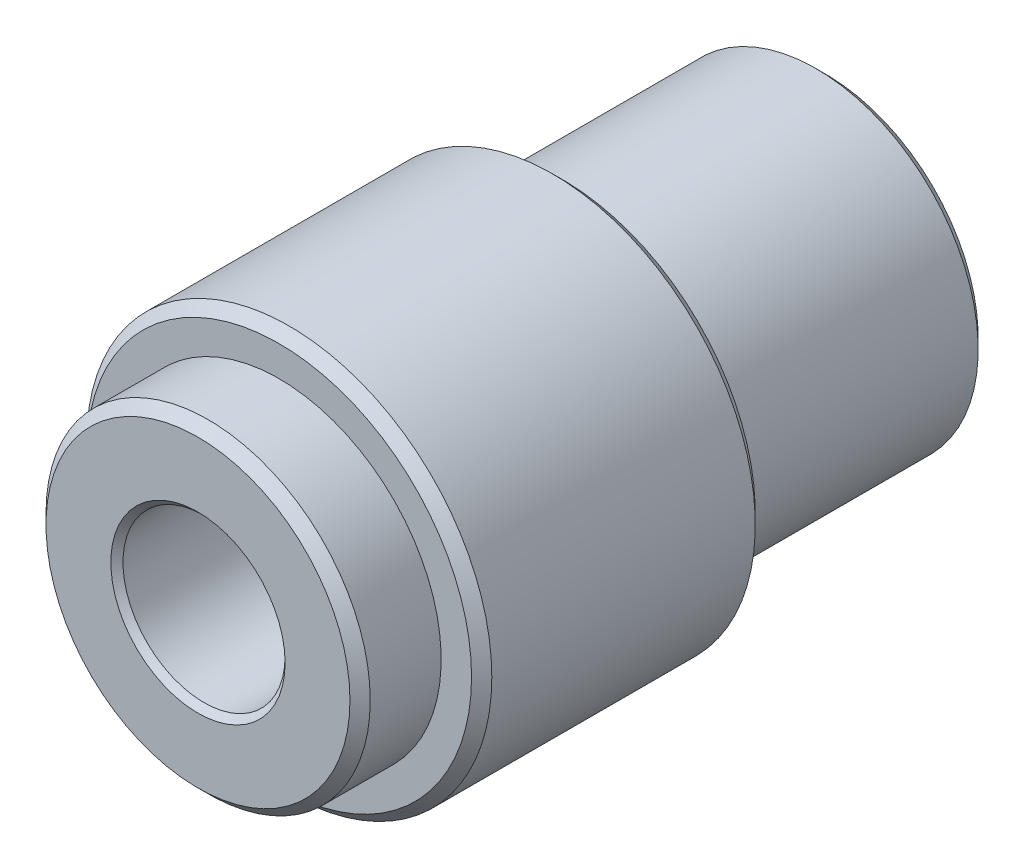
SolidWorks part; units mm, degrees
material "A2017"
ref_plane "正面" through (0, 0, 0) normal (0, 0, 1) x (1, 0, 0)
ref_plane "平面" through (0, 0, 0) normal (0, 1, 0) x (1, 0, 0)
ref_plane "右側面" through (0, 0, 0) normal (1, 0, 0) x (0, 0, -1)
sketch "ｽｹｯﾁ1" plane through (0, 0, 0) normal (1, 0, 0) x (0, 0, -1)
  line L0 (0, 0) -> (15.5, 0) construction
  line L1 (0, 0) -> (0, 4)
  line L2 (0, 4) -> (2, 4)
  line L3 (2, 4) -> (2, 5)
  line L4 (2, 5) -> (9, 5)
  line L5 (9, 5) -> (9, 4)
  line L6 (9, 4) -> (15.5, 4)
  line L7 (15.5, 4) -> (15.5, 0)
  line L8 (15.5, 0) -> (0, 0)
  dimension "D1" = 8
  dimension "D2" = 10
  dimension "D3" = 7
  dimension "D4" = 2
  dimension "D5" = 6.5
revolve "回転1" add sketch "ｽｹｯﾁ1" angle 360 about L8
chamfer "面取り1" distance 0.25 angle 45 4 edges at (-4, 0, -15.5) (-4, 0, 0) (-5, 0, -9) (-5, 0, -2)
sketch "ｽｹｯﾁ2" plane through (0, 0, 0) normal (0, 0, 1) x (1, 0, 0)
  circle A0 centre (0, 0) radius 2
  dimension "D1" = 4
extrude "ｶｯﾄ - 押し出し1" cut sketch "ｽｹｯﾁ2" against normal through all
chamfer "面取り2" distance 0.15 angle 45 2 edges at (2, 0, 0) (2, 0, -15.5)
